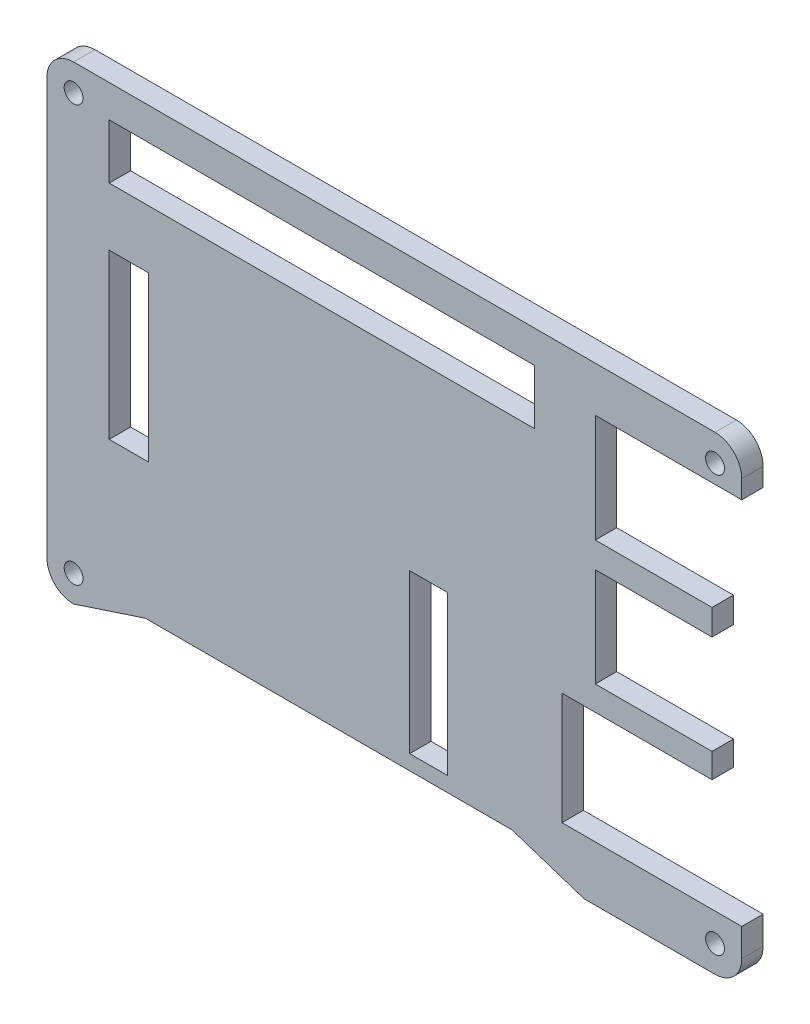
SolidWorks part; units mm, degrees
ref_plane "Front Plane" through (0, 0, 0) normal (0, 0, 1) x (1, 0, 0)
ref_plane "Top Plane" through (0, 0, 0) normal (0, 1, 0) x (1, 0, 0)
ref_plane "Right Plane" through (0, 0, 0) normal (1, 0, 0) x (0, 0, -1)
sketch "Sketch1" plane through (0, 0, 0) normal (0, 0, 1) x (1, 0, 0)
  line L0 (40.325, 24.0683) -> (61.2149, 24.0683) construction
  line L1 (61.2149, 24.0683) -> (61.2149, 26.6839) construction
  line L2 (57.4049, 30.5077) -> (-34.0849, 30.5077) construction
  line L3 (40.325, 8.6582) -> (40.325, 24.0683) construction
  line L4 (56.975, 8.6582) -> (40.325, 8.6582) construction
  line L5 (56.975, 4.9979) -> (56.975, 8.6582) construction
  line L6 (40.325, 4.9979) -> (56.975, 4.9979) construction
  line L7 (40.325, -9.1218) -> (40.325, 4.9979) construction
  line L8 (56.975, -9.1218) -> (40.325, -9.1218) construction
  line L9 (56.975, -12.628) -> (56.975, -9.1218) construction
  line L10 (35.575, -12.628) -> (56.975, -12.628) construction
  line L11 (35.575, -28.6278) -> (35.575, -12.628) construction
  line L12 (61.2149, -28.6278) -> (35.575, -28.6278) construction
  line L13 (61.2149, -32.6134) -> (61.2149, -28.6278) construction
  line L14 (38.7143, -36.451) -> (57.405, -36.451) construction
  line L15 (28.4743, -33.0844) -> (38.7143, -36.451) construction
  line L16 (-23.8449, -33.0844) -> (28.4743, -33.0844) construction
  line L17 (-34.0849, -36.451) -> (-23.8449, -33.0844) construction
  line L18 (-37.8949, 26.6977) -> (-37.8949, -32.641) construction
  line L19 (40.325, 24.0683) -> (61.2149, 24.0683)
  line L20 (61.2149, 24.0683) -> (61.2149, 26.6839)
  line L21 (57.4049, 30.5077) -> (-34.0849, 30.5077)
  line L22 (40.325, 8.6582) -> (40.325, 24.0683)
  line L23 (56.975, 8.6582) -> (40.325, 8.6582)
  line L24 (56.975, 4.9979) -> (56.975, 8.6582)
  line L25 (40.325, 4.9979) -> (56.975, 4.9979)
  line L26 (40.325, -9.1218) -> (40.325, 4.9979)
  line L27 (56.975, -9.1218) -> (40.325, -9.1218)
  line L28 (56.975, -12.628) -> (56.975, -9.1218)
  line L29 (35.575, -12.628) -> (56.975, -12.628)
  line L30 (35.575, -28.6278) -> (35.575, -12.628)
  line L31 (61.2149, -28.6278) -> (35.575, -28.6278)
  line L32 (61.2149, -32.6134) -> (61.2149, -28.6278)
  line L33 (38.7143, -36.451) -> (57.405, -36.451)
  line L34 (28.4743, -33.0844) -> (38.7143, -36.451)
  line L35 (-23.8449, -33.0844) -> (28.4743, -33.0844)
  line L36 (-34.0849, -36.451) -> (-23.8449, -33.0844)
  line L37 (-37.8949, 26.6977) -> (-37.8949, -32.641)
  line L38 (-23.4169, -23.6989) -> (-23.4169, 9.8012) construction
  line L39 (-29.0049, 25.897) -> (31.6883, 25.897)
  line L40 (-29.0049, 25.897) -> (-29.0049, 18.087)
  line L41 (-29.0049, 18.087) -> (31.6883, 18.087)
  line L42 (31.6883, 25.897) -> (31.6883, 18.087)
  line L43 (-29.0049, 9.8012) -> (-23.4169, 9.8012)
  line L44 (-29.0049, 9.8012) -> (-29.0049, -13.5668)
  line L45 (-29.0049, -13.5668) -> (-23.4169, -13.5668)
  line L46 (-23.4169, 9.8012) -> (-23.4169, -13.5668)
  line L47 (-29.0049, 9.2932) -> (-23.4169, 9.2932)
  line L50 (13.845, -8.3602) -> (19.2484, -8.3602)
  line L51 (13.845, -8.3602) -> (13.845, -30.9668)
  line L52 (13.845, -30.9668) -> (19.2484, -30.9668)
  line L53 (19.2484, -8.3602) -> (19.2484, -30.9668)
  arc A0 (61.2149, 26.6839) -> (57.4049, 30.5077) centre (57.4049, 26.6977) ccw construction
  circle A1 centre (57.4049, 26.6977) radius 1.3462 construction
  arc A2 (57.405, -36.451) -> (61.2149, -32.6134) centre (57.405, -32.641) ccw construction
  arc A3 (-37.8949, -32.641) -> (-34.0849, -36.451) centre (-34.0849, -32.641) ccw construction
  arc A4 (-34.0849, 30.5077) -> (-37.8949, 26.6977) centre (-34.0849, 26.6977) ccw construction
  circle A5 centre (-34.0849, 26.6977) radius 1.3462 construction
  circle A6 centre (-34.0849, -32.641) radius 1.3462 construction
  arc A7 (61.2149, 26.6839) -> (57.4049, 30.5077) centre (57.4049, 26.6977) ccw
  circle A8 centre (57.4049, 26.6977) radius 1.3462
  arc A9 (57.405, -36.451) -> (61.2149, -32.6134) centre (57.405, -32.641) ccw
  arc A10 (-37.8949, -32.641) -> (-34.0849, -36.451) centre (-34.0849, -32.641) ccw
  arc A11 (-34.0849, 30.5077) -> (-37.8949, 26.6977) centre (-34.0849, 26.6977) ccw
  circle A12 centre (-34.0849, 26.6977) radius 1.3462
  circle A13 centre (-34.0849, -32.641) radius 1.3462
  circle A14 centre (57.405, -32.641) radius 1.3462 construction
  circle A15 centre (57.405, -32.641) radius 1.3462
  dimension "D1" = 23.368
  dimension "D2" = 0.508
extrude "Boss-Extrude1" add sketch "Sketch1" along normal blind 3.048 contours L21 A11 L37 A10 L36 L35 L34 L33 A9 L32 L31 L30 L29 L28 L27 L26 L25 L24 L23 L22 L19 L20 A7 A15 A13 A12 L50 L53 L52 L51 L39 L42 L41 L40 L43 L46 L45 L44 A8
